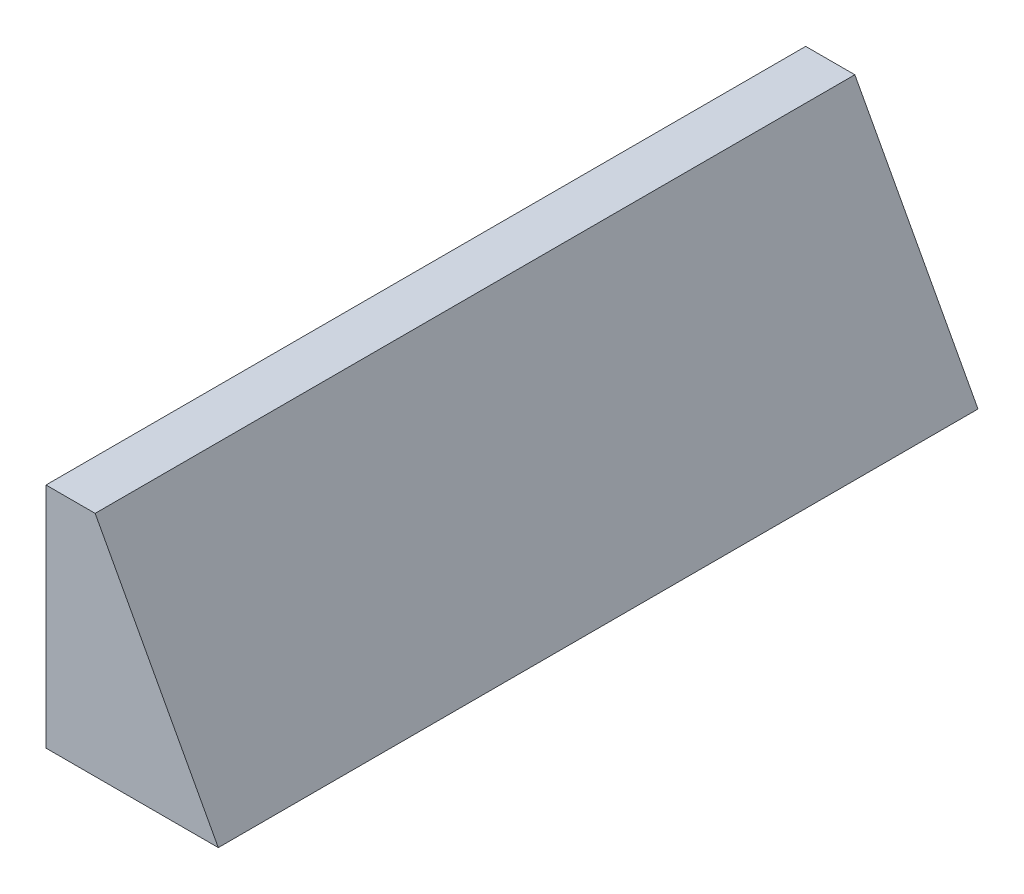
SolidWorks part; units mm, degrees
ref_plane "Front Plane" through (0, 0, 0) normal (0, 0, 1) x (1, 0, 0)
ref_plane "Top Plane" through (0, 0, 0) normal (0, 1, 0) x (1, 0, 0)
ref_plane "Right Plane" through (0, 0, 0) normal (1, 0, 0) x (0, 0, -1)
sketch "Sketch1" plane through (0, 0, 0) normal (0, 0, 1) x (1, 0, 0)
  line L0 (0, 15) -> (0, 0)
  line L1 (0, 0) -> (11.34, 0)
  line L2 (11.34, 0) -> (3.2343, 15)
  line L3 (3.2343, 15) -> (0, 15)
  dimension "D1" = 15
  dimension "D2" = 61.614
  dimension "D3" = 11.34
extrude "Boss-Extrude1" add sketch "Sketch1" along normal blind 50
